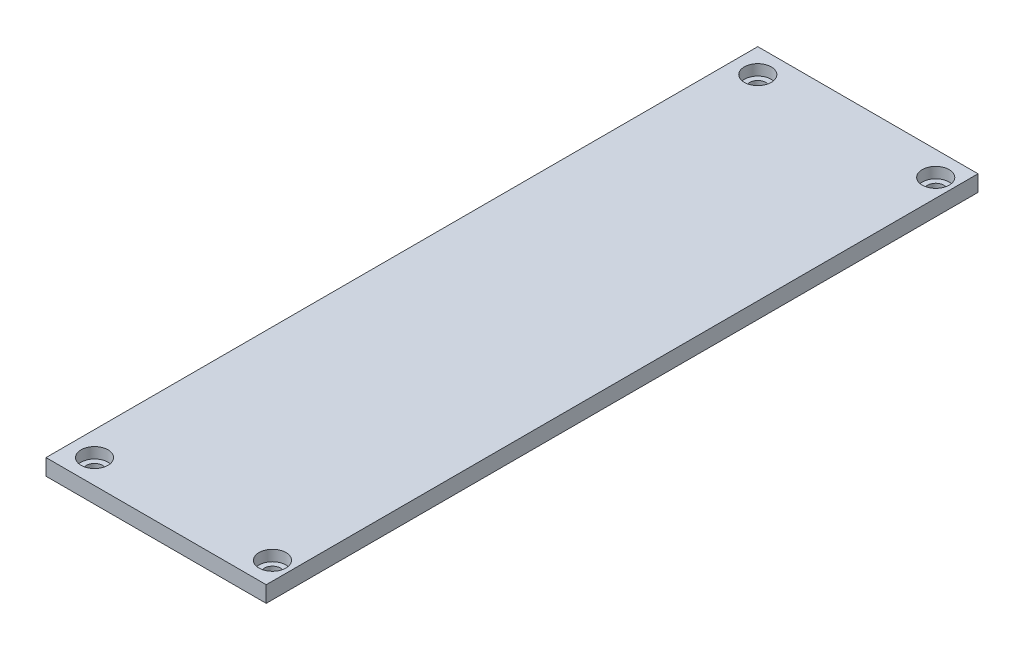
SolidWorks part; units mm, degrees
ref_plane "Front Plane" through (0, 0, 0) normal (0, 0, 1) x (1, 0, 0)
ref_plane "Top Plane" through (0, 0, 0) normal (0, 1, 0) x (1, 0, 0)
ref_plane "Right Plane" through (0, 0, 0) normal (1, 0, 0) x (0, 0, -1)
sketch "Sketch1" plane through (0, 0, 0) normal (0, 1, 0) x (1, 0, 0)
  line L1 (-21, 66) -> (21, 66)
  line L2 (-21, 66) -> (-21, -66)
  line L3 (-21, -66) -> (21, -66)
  line L4 (21, 66) -> (21, -66)
  line L5 (-21, 66) -> (21, -66) construction
  line L6 (-21, -66) -> (21, 66) construction
  point P0 (0, 0)
  dimension "D1" = 42
  dimension "D2" = 132
extrude "Boss-Extrude1" add sketch "Sketch1" along normal blind 3
sketch "Sketch2" plane through (0, 3, 0) normal (0, 1, 0) x (1, 0, 0)
  line L0 (-21, 66) -> (-21, -66) construction
  line L1 (21, 66) -> (-21, 66) construction
  line L2 (21, -66) -> (21, 66) construction
  line L3 (-21, -66) -> (21, -66) construction
  circle A0 centre (-16.5, 61.5) radius 2.5
  circle A1 centre (16.5, 61.5) radius 2.5
  circle A2 centre (16.5, -61.5) radius 2.5
  circle A3 centre (-16.5, -61.5) radius 2.5
  point P0 (-16.5, 61.5)
  point P1 (16.5, 61.5)
  point P2 (16.5, -61.5)
  point P3 (-16.5, -61.5)
  dimension "D9" = 5
  dimension "D10" = 5
  dimension "D11" = 5
  dimension "D12" = 5
  dimension "D1" = 4.5
  dimension "D2" = 4.5
  dimension "D3" = 4.5
  dimension "D4" = 4.5
  dimension "D5" = 4.5
  dimension "D6" = 4.5
  dimension "D7" = 4.5
  dimension "D8" = 4.5
extrude "Cut-Extrude1" cut sketch "Sketch2" against normal blind 2
sketch "Sketch3" plane through (0, 1, 0) normal (0, 1, 0) x (1, 0, 0)
  circle A0 centre (-16.5, 61.5) radius 1.5
  circle A1 centre (16.5, 61.5) radius 1.5
  circle A2 centre (16.5, -61.5) radius 1.5
  circle A3 centre (-16.5, -61.5) radius 1.5
  dimension "D1" = 3
  dimension "D2" = 3
  dimension "D3" = 3
  dimension "D4" = 3
extrude "Cut-Extrude2" cut sketch "Sketch3" against normal through all
sketch "Sketch4" plane through (0, 3, 0) normal (0, 1, 0) x (1, 0, 0)
  line L1 (21, -66) -> (21, 66) construction
  line L9 (19.8402, 66) -> (19.8402, -66)
  line L10 (21, 66) -> (-21, 66) construction
  line L11 (-21, -66) -> (21, -66) construction
  line L12 (21, -66) -> (21, 66)
  line L13 (21, 66) -> (19.8402, 66)
extrude "Cut-Extrude3" cut sketch "Sketch4" against normal through all
